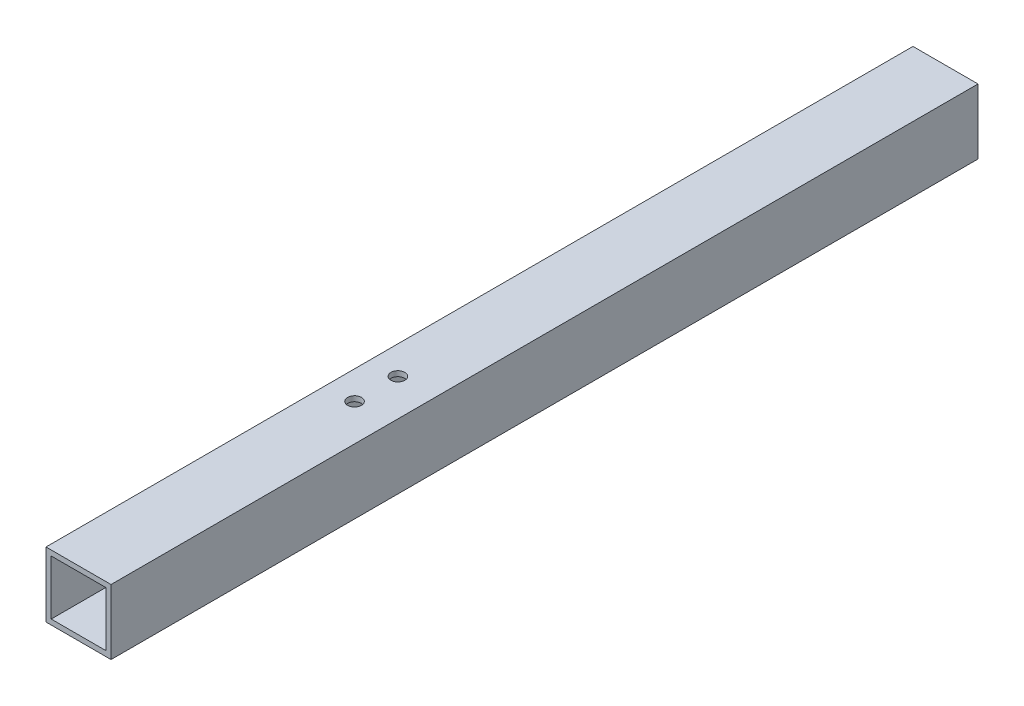
SolidWorks part; units mm, degrees
material "7050-T73510"
ref_plane "Front" through (0, 0, 0) normal (0, 0, 1) x (1, 0, 0)
ref_plane "Top" through (0, 0, 0) normal (0, 1, 0) x (1, 0, 0)
ref_plane "Right" through (0, 0, 0) normal (1, 0, 0) x (0, 0, -1)
sketch "草图1" plane through (0, 0, 0) normal (0, 0, 1) x (1, 0, 0)
  line L0 (-6.3, -6.3) -> (-6.3, 6.3)
  line L1 (-7.5, -7.5) -> (7.5, -7.5)
  line L2 (-7.5, -7.5) -> (-7.5, 7.5)
  line L3 (-7.5, 7.5) -> (7.5, 7.5)
  line L4 (7.5, -7.5) -> (7.5, 7.5)
  line L5 (-7.5, -7.5) -> (7.5, 7.5) construction
  line L6 (-7.5, 7.5) -> (7.5, -7.5) construction
  line L7 (-6.3, 6.3) -> (6.3, 6.3)
  line L8 (6.3, -6.3) -> (6.3, 6.3)
  line L9 (-6.3, -6.3) -> (6.3, -6.3)
  point P0 (0, 0)
  dimension "D1" = 15
  dimension "D2" = 15
  dimension "D3" = 1.2
extrude "凸台-拉伸1" add sketch "草图1" along normal blind 200
sketch "草图2" plane through (0, -7.5, 0) normal (0, -1, 0) x (1, 0, 0)
  circle A4 centre (-1, 135.3224) radius 1.6
  circle A5 centre (-1, 125.3224) radius 1.6
extrude "切除-拉伸1" cut sketch "草图2" against normal blind 25
